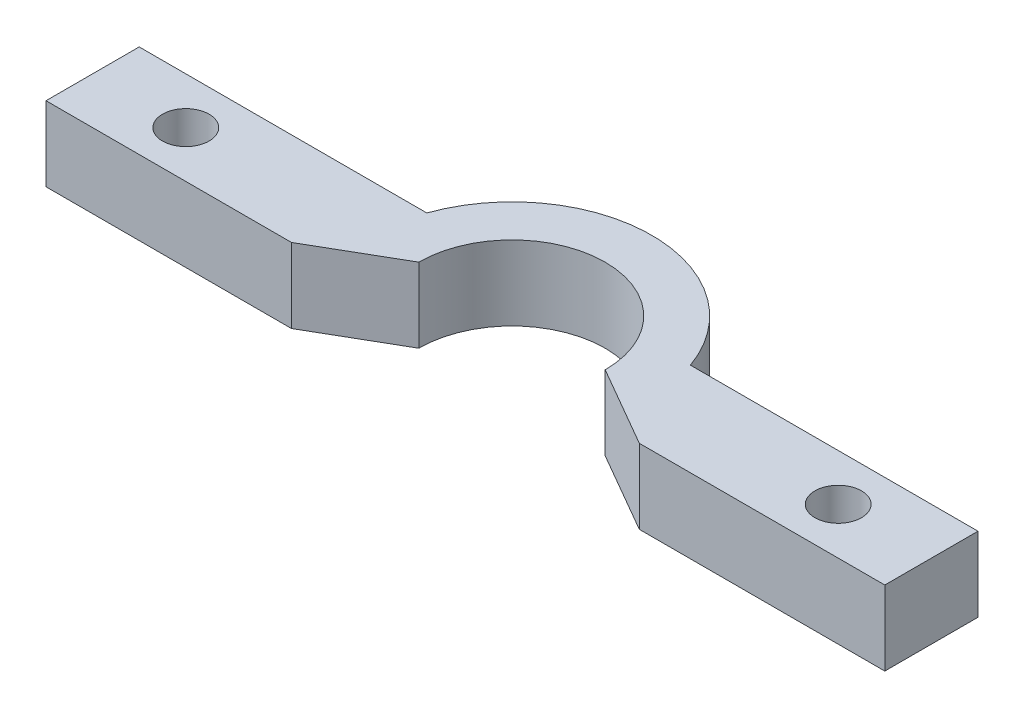
SolidWorks part; units mm, degrees
ref_plane "Front Plane" through (0, 0, 0) normal (0, 0, 1) x (1, 0, 0)
ref_plane "Top Plane" through (0, 0, 0) normal (0, 1, 0) x (1, 0, 0)
ref_plane "Right Plane" through (0, 0, 0) normal (1, 0, 0) x (0, 0, -1)
sketch "Sketch1" plane through (0, 0, 0) normal (0, 1, 0) x (1, 0, 0)
  line L0 (0, 0) -> (4.7625, 0)
  line L1 (-14.2875, -1.5875) -> (14.2875, -1.5875)
  line L2 (-14.2875, -1.5875) -> (-14.2875, 1.5875)
  line L3 (-14.2875, 1.5875) -> (14.2875, 1.5875)
  line L4 (14.2875, -1.5875) -> (14.2875, 1.5875)
  line L5 (-14.2875, -1.5875) -> (14.2875, 1.5875) construction
  line L6 (-14.2875, 1.5875) -> (14.2875, -1.5875) construction
  line L7 (4.7625, 0) -> (-4.7625, 0)
  line L8 (-3.175, 0) -> (-5.9246, -1.5875)
  line L9 (-5.9246, -1.5875) -> (5.9246, -1.5875)
  line L10 (5.9246, -1.5875) -> (3.175, 0)
  circle A0 centre (0, 0) radius 4.7625
  circle A1 centre (0, 0) radius 3.175
  circle A2 centre (-11.1125, 0) radius 0.7937
  circle A3 centre (11.1125, 0) radius 0.7937
  point P0 (0, 0)
  dimension "D3" = 1.5875
  dimension "D4" = 9.525
  dimension "D6" = 1.5875
  dimension "D7" = 3.175
  dimension "D1" = 28.575
  dimension "D2" = 3.175
  dimension "D5" = 3.175
  dimension "D8" = 3.175
extrude "Boss-Extrude1" add sketch "Sketch1" along normal mid plane 2.54
